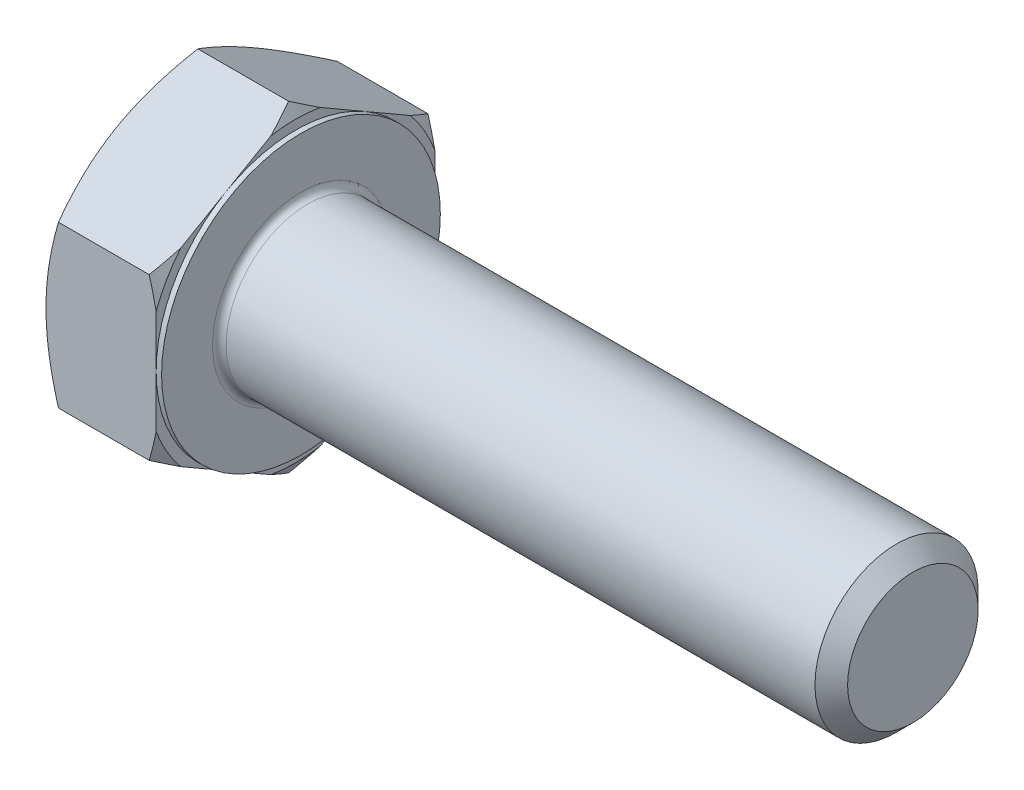
SolidWorks part; units mm, degrees
extrude "基体-拉伸" add sketch "草图1" along normal blind 17
sketch "草图1" plane through (0, 0, 0) normal (1, 0, 0) x (0, 0, -1)
  line L0 (20.5, 11.8357) -> (20.5, -11.8357)
  line L1 (-20.5, 11.8357) -> (-20.5, -11.8357)
  line L2 (20.5, -11.8357) -> (0, -23.6714)
  line L3 (0, -23.6714) -> (-20.5, -11.8357)
  line L4 (20.5, 11.8357) -> (0, 23.6714)
  line L5 (0, 23.6714) -> (-20.5, 11.8357)
  dimension "s" = 41
  dimension "D2" = 120
  dimension "D3" = 20.5
  dimension "D4" = 20.5
  dimension "D5" = 20.5
revolve "切除-旋转1" cut sketch "草图3" angle 360 about L6
sketch "草图3" plane through (0, 0, 0) normal (0, 0, 1) x (1, 0, 0)
  line L0 (0, 20.5) -> (4.7177, 28.6714)
  line L1 (0, 23.6714) -> (0, 11.8357) construction
  line L2 (4.7177, 28.6714) -> (4.7177, 33.6714)
  line L3 (4.7177, 33.6714) -> (-10, 33.6714)
  line L4 (-10, 33.6714) -> (-10, 20.5)
  line L5 (-10, 20.5) -> (0, 20.5)
  line L6 (0, 0) -> (99.06, 0) construction
  line L7 (17, 23.6714) -> (0, 23.6714) construction
  dimension "D1" = 20.5
  dimension "D2" = 5
  dimension "D3" = 10
  dimension "D4" = 5
  dimension "Head_ch_ang" = 30
revolve "凸台-旋转1" add sketch "草图2" angle 360 about L7
sketch "草图2" plane through (0, 0, 0) normal (0, 0, 1) x (1, 0, 0)
  line L0 (0, 11.8357) -> (0, -11.8357) construction
  line L1 (0, 0) -> (107, 0)
  line L2 (0, 0) -> (0, 12)
  line L3 (0, 12) -> (107, 12)
  line L4 (107, 0) -> (107, 9.402)
  line L5 (17, 23.6714) -> (17, 11.8357) construction
  line L7 (0, 0) -> (96.52, 0) construction
  line L8 (107, -9.402) -> (90.335, -12) construction
  line L9 (0, -12) -> (90.335, -12) construction
  line L10 (20, 15.24) -> (20, -1.27) construction
  line L11 (17, 15.24) -> (17, -1.27) construction
  line L12 (17, 11.8357) -> (17, -11.8357) construction
  line L14 (107, 12) -> (107, 9.402)
  dimension "l" = 90
  dimension "m" = 24
  dimension "Minor_dia" = 18.804
  dimension "p" = 3
  dimension "h" = 90
cosmetic thread "螺旋线1" parameters "Thread_length"=87, "Thread_minor"=18.804
material "5.6级"
ref_plane "前视" through (0, 0, 0) normal (0, 0, 1) x (1, 0, 0)
ref_plane "上视" through (0, 0, 0) normal (0, 1, 0) x (1, 0, 0)
ref_plane "右视" through (0, 0, 0) normal (1, 0, 0) x (0, 0, -1)
sketch "草图5" plane through (0, 0, 0) normal (0, 0, 1) x (1, 0, 0)
  line L0 (17, 20.5) -> (12.2823, 28.6714)
  line L1 (17, 23.6714) -> (17, 11.8357) construction
  line L2 (12.2823, 28.6714) -> (12.2823, 33.6714)
  line L3 (12.2823, 33.6714) -> (22.2823, 33.6714)
  line L4 (22.2823, 33.6714) -> (22.2823, 20.5)
  line L5 (22.2823, 20.5) -> (17, 20.5)
  line L7 (17, 23.6714) -> (1.831, 23.6714) construction
  line L8 (0, 0) -> (99.06, 0) construction
  line L9 (0, 0) -> (99.06, 0) construction
  dimension "D1" = 20.5
  dimension "D2" = 5
  dimension "D3" = 10
  dimension "D4" = 5
  dimension "Head_ch_ang" = 30
revolve "切除-旋转2" cut sketch "草图5" angle 360 about L8
sketch "草图4" plane through (0, 0, 0) normal (0, 0, 1) x (1, 0, 0)
  line L1 (17, 23.6714) -> (17, 11.8357) construction
  line L2 (17, 20.5) -> (16.2, 20.5)
  line L3 (17, 20.5) -> (17, 33.6714)
  line L4 (17, 33.6714) -> (16.2, 33.6714)
  line L5 (0, 0) -> (95.25, 0) construction
  line L6 (0, 0) -> (96.52, 0) construction
  line L7 (16.2, 20.5) -> (16.2, 33.6714)
  line L8 (15.169, 23.6714) -> (1.831, 23.6714) construction
  dimension "D2" = 10
  dimension "D1" = 41
revolve "切除-旋转3" cut sketch "草图4" angle 360 about L5
chamfer "倒角" distance 2.4 angle 45 1 edges at (107, 0, 12)
fillet "圆角" radius 1 1 edges at (17, 0, -12)
sketch "草图6" plane through (0, 0, 0) normal (0, 0, 1) x (1, 0, 0)
  line L0 (19.5, -9.402) -> (18, -12)
  line L1 (19.5, -9.402) -> (20.9999, -12)
  line L2 (20.9999, -12) -> (20.9999, -15)
  line L3 (-3.175, 0) -> (5.1513, 0) construction
  line L5 (20.9999, -15) -> (18, -15)
  line L6 (18, -15) -> (18, -12)
  arc A0 (18, -12) -> (17, -13) centre (18, -13) ccw construction
  dimension "Thread_minor" = 18.804
  dimension "Diameter" = 24
revolve "切除-旋转4" [suppressed] cut sketch "草图6" angle 360 about L3
pattern_linear "阵列(线性)1" [suppressed]
equation "\"D3@草图1\" = \"s@草图1\" / 2"
equation "\"D4@草图1\" = \"D3@草图1\""
equation "\"D5@草图1\" = \"D4@草图1\""
equation "\"D1@草图3\" = \"s@草图1\" / 2"
equation "\"D1@草图5\" = \"s@草图1\" / 2"
equation "\"Head_ch_ang@草图5\" = \"Head_ch_ang@草图3\""
equation "\"D1@草图4\" = \"s@草图1\""
equation "\"Diameter@草图6\" = \"m@草图2\""
equation "\"Overcut@草图6\" = \"m@草图2\" * 1.25"
equation "\"Minor_dia@草图2\" = \"m@草图2\"-\"p@草图2\" * 1.732"
equation "\"Thread_minor@螺旋线1\" = \"Minor_dia@草图2\""
equation "\"Thread_minor@草图6\" = \"Minor_dia@草图2\""
equation "\"D1@倒角\" = \"p@草图2\"*0.8"
equation "\"Thread_length@螺旋线1\" = \"l@草图2\" - \"p@草图2\""
equation "\"Num_threads@阵列(线性)1\" = \"l@草图2\" / \"p@草图2\""
